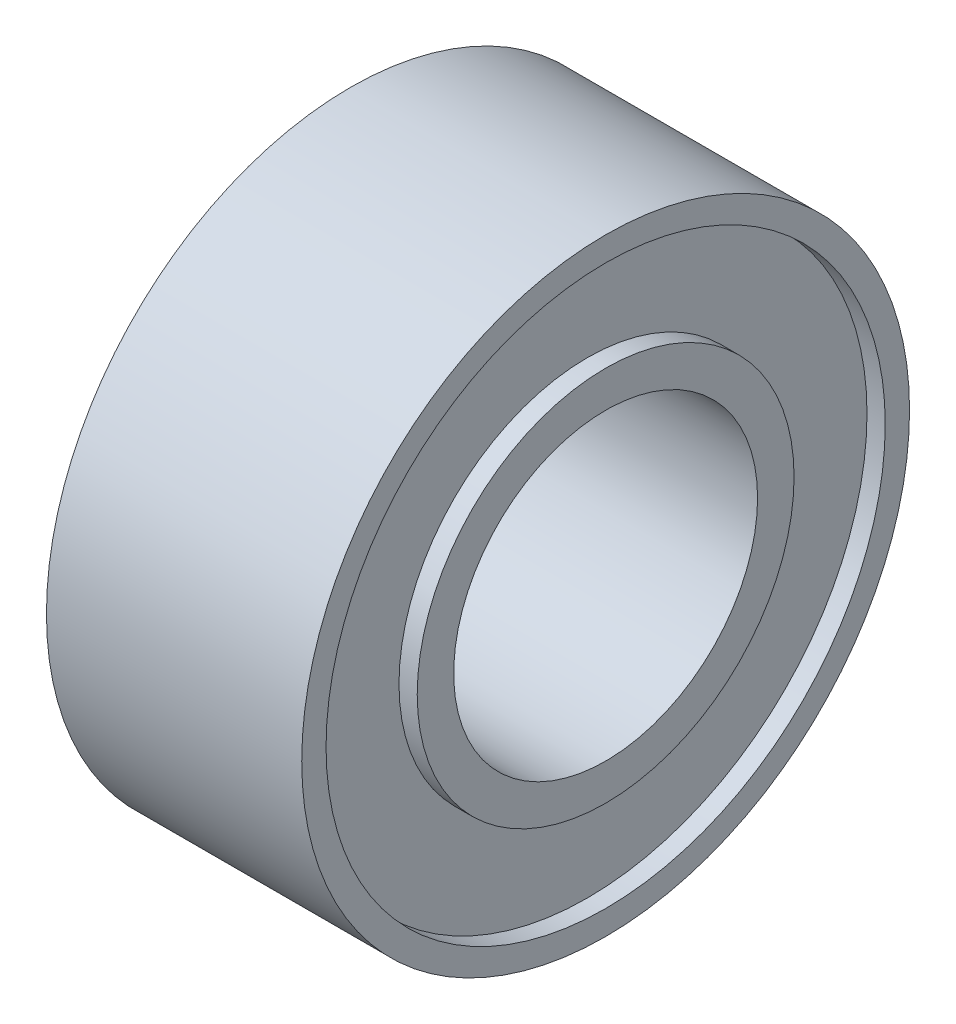
SolidWorks part; units mm, degrees
material "Stainless Steel (ferritic)"
ref_plane "Front Plane" through (0, 0, 0) normal (0, 0, 1) x (1, 0, 0)
ref_plane "Top Plane" through (0, 0, 0) normal (0, 1, 0) x (1, 0, 0)
ref_plane "Right Plane" through (0, 0, 0) normal (1, 0, 0) x (0, 0, -1)
sketch "Sketch1" plane through (0, 0, 0) normal (0, 0, 1) x (1, 0, 0)
  line L0 (-2.1, 3.1) -> (-2.1, 2.5)
  line L1 (-2.1, 2.5) -> (2.1, 2.5)
  line L2 (2.1, 2.5) -> (2.1, 3.1)
  line L3 (2.1, 3.1) -> (1.8, 3.1)
  line L4 (1.8, 3.1) -> (1.8, 4.6)
  line L5 (1.8, 4.6) -> (2.1, 4.6)
  line L6 (2.1, 4.6) -> (2.1, 5)
  line L7 (2.1, 5) -> (-2.1, 5)
  line L8 (-2.1, 5) -> (-2.1, 4.6)
  line L9 (-2.1, 4.6) -> (-1.8, 4.6)
  line L10 (-1.8, 4.6) -> (-1.8, 3.1)
  line L11 (-1.8, 3.1) -> (-2.1, 3.1)
  line L12 (-2.1, 0) -> (2.1, 0) construction
revolve "Revolve1" add sketch "Sketch1" angle 360 about L12
